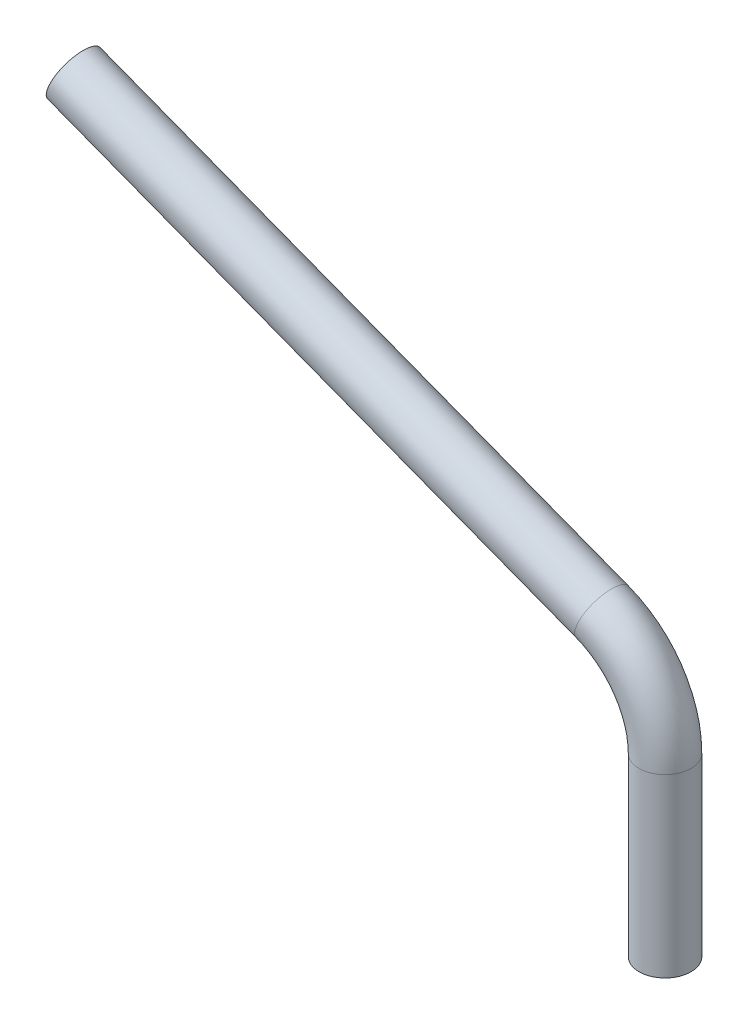
SolidWorks part; units mm, degrees
material "Launcher Hook"
ref_plane "Front Plane" through (0, 0, 0) normal (0, 0, 1) x (1, 0, 0)
ref_plane "Top Plane" through (0, 0, 0) normal (0, 1, 0) x (1, 0, 0)
ref_plane "Right Plane" through (0, 0, 0) normal (1, 0, 0) x (0, 0, -1)
sketch "Sketch1" plane through (0, 0, 0) normal (0, 0, 1) x (1, 0, 0)
  line L0 (-35.814, 28.448) -> (-3.81, 16.2048)
  line L1 (0, 10.668) -> (0, 0)
  line L2 (0, 10.668) -> (0, 19.2158) construction
  arc A0 (-3.81, 16.2048) -> (0, 10.668) centre (-5.9281, 10.668) cw
  dimension "D1" = 35.814
  dimension "D2" = 3.81
  dimension "D3" = 17.78
  dimension "D4" = 10.668
sketch "Sketch2" plane through (0, 0, 0) normal (0, 1, 0) x (1, 0, 0)
  circle A0 centre (0, 0) radius 1.5748
  dimension "D1" = 3.1496
sweep "Sweep1" add profiles "Sketch2" path "Sketch1"
